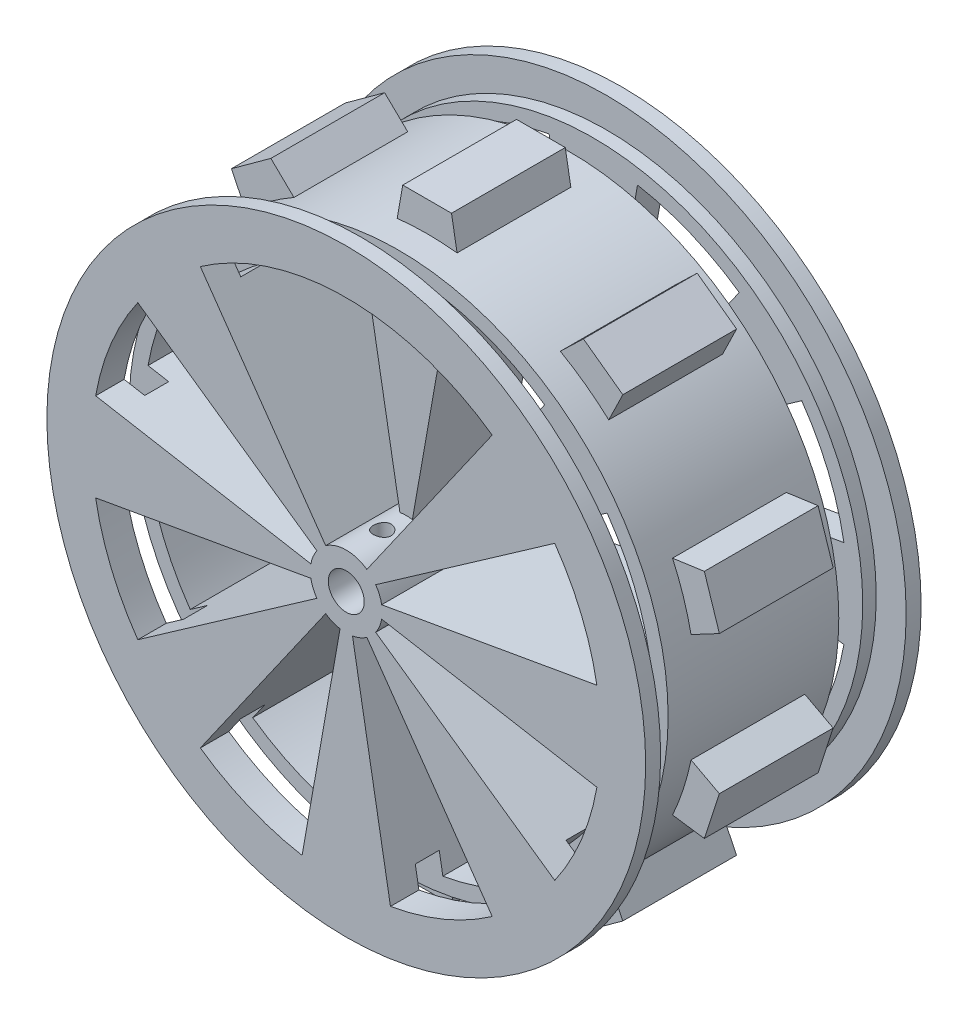
SolidWorks part; units mm, degrees
material "Resina de melamina"
ref_plane "Alzado" through (0, 0, 0) normal (0, 0, 1) x (1, 0, 0)
ref_plane "Planta" through (0, 0, 0) normal (0, 1, 0) x (1, 0, 0)
ref_plane "Vista lateral" through (0, 0, 0) normal (1, 0, 0) x (0, 0, -1)
sketch "Croquis2" plane through (0, 0, 0) normal (0, 0, 1) x (1, 0, 0)
  circle A0 centre (0, 0) radius 45
  circle A1 centre (0, 0) radius 7.5
  dimension "D1" = 90
  dimension "D2" = 15
extrude "Saliente-Extruir1" add sketch "Croquis2" along normal blind 40
ref_plane "Plano1" through (0, 0, 20) normal (0, 0, 1) x (1, 0, 0)
sketch "Croquis3" plane through (0, 0, 20) normal (0, 0, 1) x (1, 0, 0)
  line L32 (26.1006, 42.8402) -> (22.2452, 39.1171)
  line L35 (0, 50) -> (4.0735, 50)
  line L36 (0, 50) -> (-4.065, 50)
  line L37 (-4.065, 50) -> (-4.9957, 44.7218)
  line L38 (4.0735, 50) -> (5.0043, 44.7209)
  line L39 (29.3893, 40.4508) -> (26.1006, 42.8402)
  line L40 (29.3893, 40.4508) -> (32.6848, 38.0565)
  line L41 (32.6848, 38.0565) -> (30.3349, 33.2385)
  line L42 (46.2967, 19.3169) -> (40.9892, 18.571)
  line L43 (47.5528, 15.4508) -> (46.2967, 19.3169)
  line L44 (47.5528, 15.4508) -> (48.8116, 11.5768)
  line L45 (48.8116, 11.5768) -> (44.0785, 9.0601)
  line L46 (48.809, -11.5848) -> (44.0767, -9.0686)
  line L47 (47.5528, -15.4508) -> (48.809, -11.5848)
  line L48 (47.5528, -15.4508) -> (46.2941, -19.3249)
  line L49 (46.2941, -19.3249) -> (40.9857, -18.5789)
  line L50 (32.6779, -38.0615) -> (30.3284, -33.2443)
  line L51 (29.3893, -40.4508) -> (32.6779, -38.0615)
  line L52 (29.3893, -40.4508) -> (26.0938, -42.8452)
  line L53 (26.0938, -42.8452) -> (22.2377, -39.1214)
  line L54 (4.065, -50) -> (4.9957, -44.7218)
  line L55 (0, -50) -> (4.065, -50)
  line L56 (0, -50) -> (-4.0735, -50)
  line L57 (-4.0735, -50) -> (-5.0043, -44.7209)
  line L58 (-26.1006, -42.8402) -> (-22.2452, -39.1171)
  line L59 (-29.3893, -40.4508) -> (-26.1006, -42.8402)
  line L60 (-29.3893, -40.4508) -> (-32.6848, -38.0565)
  line L61 (-32.6848, -38.0565) -> (-30.3349, -33.2385)
  line L62 (-46.2967, -19.3169) -> (-40.9892, -18.571)
  line L63 (-47.5528, -15.4508) -> (-46.2967, -19.3169)
  line L64 (-47.5528, -15.4508) -> (-48.8116, -11.5768)
  line L65 (-48.8116, -11.5768) -> (-44.0785, -9.0601)
  line L66 (-48.809, 11.5848) -> (-44.0767, 9.0686)
  line L67 (-47.5528, 15.4508) -> (-48.809, 11.5848)
  line L68 (-47.5528, 15.4508) -> (-46.2941, 19.3249)
  line L69 (-46.2941, 19.3249) -> (-40.9857, 18.5789)
  line L70 (-32.6779, 38.0615) -> (-30.3284, 33.2443)
  line L71 (-29.3893, 40.4508) -> (-32.6779, 38.0615)
  line L72 (-29.3893, 40.4508) -> (-26.0938, 42.8452)
  line L73 (-26.0938, 42.8452) -> (-22.2377, 39.1214)
  circle A9 centre (0, 0) radius 45
  dimension "D3" = 80
  dimension "D5" = 4.065
  dimension "D1" = 18.2536
  dimension "D2" = 80
  dimension "D4" = 10
  dimension "D6" = 4.0735
  dimension "D7" = 10.0207
extrude "Saliente-Extruir2" add sketch "Croquis3" along normal blind 9.5 and the other way blind 9.5 contours A9 L38 L35 L36 L37 | A9 L41 L40 L39 L32 | A9 L45 L44 L43 L42 | A9 L49 L48 L47 L46 | A9 L53 L52 L51 L50 | A9 L57 L56 L55 L54 | A9 L61 L60 L59 L58 | A9 L65 L64 L63 L62 | A9 L73 L72 L71 L70 | A9 L69 L68 L67 L66
sketch "Croquis4" plane through (0, 0, 40) normal (0, 0, 1) x (1, 0, 0)
  circle A0 centre (0, 0) radius 42.5
extrude "Cortar-Extruir1" cut sketch "Croquis4" against normal blind 58
sketch "Croquis5" plane through (0, 0, 40) normal (0, 0, 1) x (1, 0, 0)
  circle A0 centre (0, 0) radius 42.5
  circle A1 centre (0, 0) radius 50
extrude "Saliente-Extruir3" add sketch "Croquis5" along normal blind 3
sketch "Croquis6" plane through (0, 0, 40) normal (0, 0, -1) x (-1, 0, 0)
  circle A0 centre (0, 0) radius 45
  circle A1 centre (0, 0) radius 50
extrude "Cortar-Extruir2" cut sketch "Croquis6" against normal blind 0.5
sketch "Croquis7" plane through (0, 0, 0) normal (0, 0, -1) x (-1, 0, 0)
  circle A0 centre (0, 0) radius 42.5
  circle A1 centre (0, 0) radius 50
extrude "Saliente-Extruir4" add sketch "Croquis7" along normal blind 3
sketch "Croquis8" plane through (0, 0, 0) normal (0, 0, 1) x (1, 0, 0)
  circle A0 centre (0, 0) radius 45
  circle A1 centre (0, 0) radius 50
extrude "Cortar-Extruir3" cut sketch "Croquis8" against normal blind 0.5
sketch "Croquis9" plane through (0, 0, 43) normal (0, 0, 1) x (1, 0, 0)
  line L17 (5.9088, -1.0419) -> (41.8543, -7.38)
  line L18 (5.9088, 1.0419) -> (41.8543, 7.38)
  line L19 (4.9149, 3.4415) -> (34.814, 24.377)
  line L20 (3.4415, 4.9149) -> (24.377, 34.814)
  line L21 (1.0419, 5.9088) -> (7.38, 41.8543)
  line L22 (0, 6) -> (0, 42.5) construction
  line L23 (-1.0419, 5.9088) -> (-7.38, 41.8543)
  line L24 (-3.4415, 4.9149) -> (-24.377, 34.814)
  line L25 (-4.9149, 3.4415) -> (-34.814, 24.377)
  line L26 (-5.9088, 1.0419) -> (-41.8543, 7.38)
  line L27 (-5.9088, -1.0419) -> (-41.8543, -7.38)
  line L28 (-4.9149, -3.4415) -> (-34.814, -24.377)
  line L29 (-3.4415, -4.9149) -> (-24.377, -34.814)
  line L30 (-1.0419, -5.9088) -> (-7.38, -41.8543)
  line L31 (1.0419, -5.9088) -> (7.38, -41.8543)
  line L32 (3.4415, -4.9149) -> (24.377, -34.814)
  line L33 (4.9149, -3.4415) -> (34.814, -24.377)
  circle A0 centre (0, 0) radius 3
  arc A1 (7.38, 41.8543) -> (-7.38, 41.8543) centre (0, 0) ccw
  arc A2 (34.814, 24.377) -> (24.377, 34.814) centre (0, 0) ccw
  arc A3 (41.8543, -7.38) -> (41.8543, 7.38) centre (0, 0) ccw
  arc A4 (24.377, -34.814) -> (34.814, -24.377) centre (0, 0) ccw
  arc A5 (-7.38, -41.8543) -> (7.38, -41.8543) centre (0, 0) ccw
  arc A6 (-34.814, -24.377) -> (-24.377, -34.814) centre (0, 0) ccw
  arc A7 (-41.8543, 7.38) -> (-41.8543, -7.38) centre (0, 0) ccw
  arc A8 (-24.377, 34.814) -> (-34.814, 24.377) centre (0, 0) ccw
  arc A9 (-1.0419, 5.9088) -> (-3.4415, 4.9149) centre (0, 0) ccw
  arc A10 (-4.9149, 3.4415) -> (-5.9088, 1.0419) centre (0, 0) ccw
  arc A11 (-5.9088, -1.0419) -> (-4.9149, -3.4415) centre (0, 0) ccw
  arc A12 (-3.4415, -4.9149) -> (-1.0419, -5.9088) centre (0, 0) ccw
  arc A13 (1.0419, -5.9088) -> (3.4415, -4.9149) centre (0, 0) ccw
  arc A14 (4.9149, -3.4415) -> (5.9088, -1.0419) centre (0, 0) ccw
  arc A15 (5.9088, 1.0419) -> (4.9149, 3.4415) centre (0, 0) ccw
  arc A16 (3.4415, 4.9149) -> (1.0419, 5.9088) centre (0, 0) ccw
  dimension "D1" = 6
  dimension "D5" = 12
  dimension "D4" = 8
extrude "Saliente-Extruir5" add sketch "Croquis9" against normal through all
sketch "Croquis11" plane through (0, 0, 43) normal (0, 0, 1) x (1, 0, 0)
  line L0 (7.38, 41.8543) -> (1.0419, 5.9088)
  line L1 (-7.38, 41.8543) -> (-1.0419, 5.9088)
  arc A0 (1.0419, 5.9088) -> (-1.0419, 5.9088) centre (0, 0) ccw
  arc A1 (7.38, 41.8543) -> (-7.38, 41.8543) centre (0, 0) ccw
extrude "Cortar-Extruir5" cut sketch "Croquis11" against normal blind 10
ref_plane "Plano2" through (0, 7, 0) normal (0, 1, 0) x (1, 0, 0)
sketch "Croquis13" plane through (0, 7, 0) normal (0, 1, 0) x (1, 0, 0)
  line L0 (0, -33) -> (0, -37) construction
  line L1 (-1.0419, -33) -> (1.0419, -33) construction
  circle A0 centre (0, -37) radius 1.5
  dimension "D2" = 3
  dimension "D1" = 4
extrude "Cortar-Extruir7" cut sketch "Croquis13" against normal blind 7
sketch "Croquis14" plane through (0, 0, 33) normal (0, 0, 1) x (1, 0, 0)
  line L0 (0, 3) -> (0, 6) construction
  circle A0 centre (0, 0) radius 3 construction
  arc A1 (3.4415, 4.9149) -> (-3.4415, 4.9149) centre (0, 0) ccw construction
sketch "Croquis15" plane through (0, 0, 0) normal (0, 1, 0) x (1, 0, 0)
  line L0 (-45, 0.5) -> (-45, -1.75) construction
  line L5 (-45, 0.5) -> (-45, -40.5) construction
  line L6 (-69.4705, -20) -> (-11.923, -20) construction
  line L7 (-45, -1.75) -> (-39, -1.75)
  line L8 (-45, -1.75) -> (-45, -5.75)
  line L9 (-45, -5.75) -> (-39, -5.75)
  line L10 (-39, -1.75) -> (-39, -5.75)
  line L11 (-55, -20) -> (55, -20) construction
  line L12 (-45, -40.5) -> (-45, -38.25) construction
  line L13 (-39, -38.25) -> (-39, -34.25)
  line L14 (-45, -34.25) -> (-39, -34.25)
  line L15 (-45, -38.25) -> (-45, -34.25)
  line L16 (-45, -38.25) -> (-39, -38.25)
  line L17 (0, 0) -> (0, 33.795) construction
  dimension "D1" = 2.25
  dimension "D2" = 6
  dimension "D3" = 4
revolve "Cortar-Revolución1" cut sketch "Croquis15" angle 360 about L17
sketch "Croquis16" plane through (0, 0, -3) normal (0, 0, -1) x (-1, 0, 0)
  circle A0 centre (0, 0) radius 30
  dimension "D1" = 60
extrude "Cortar-Extruir8" cut sketch "Croquis16" against normal blind 20
